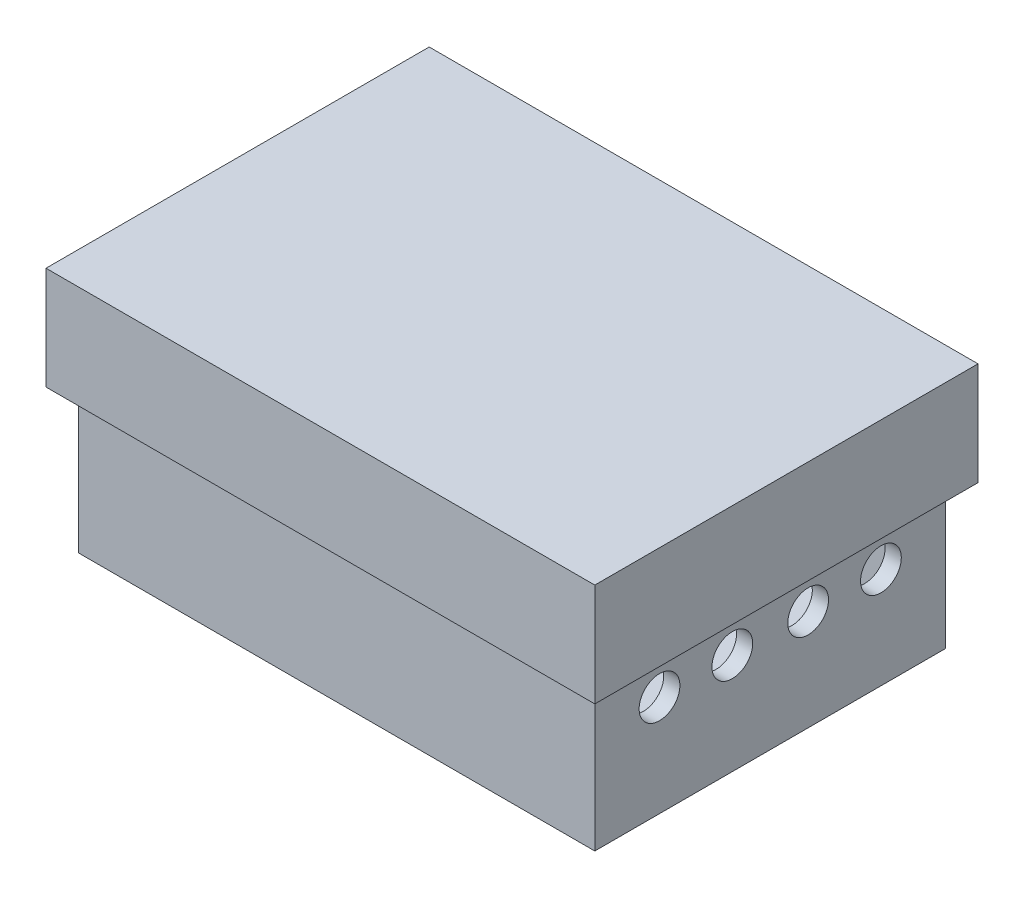
SolidWorks part; units mm, degrees
ref_plane "Front Plane" through (0, 0, 0) normal (0, 0, 1) x (1, 0, 0)
ref_plane "Top Plane" through (0, 0, 0) normal (0, 1, 0) x (1, 0, 0)
ref_plane "Right Plane" through (0, 0, 0) normal (1, 0, 0) x (0, 0, -1)
sketch "Sketch1" plane through (0, 0, 0) normal (0, 1, 0) x (1, 0, 0)
  line L1 (-95, 62.5) -> (95, 62.5)
  line L2 (-95, 62.5) -> (-95, -62.5)
  line L3 (-95, -62.5) -> (95, -62.5)
  line L4 (95, 62.5) -> (95, -62.5)
  line L5 (-95, 62.5) -> (95, -62.5) construction
  line L6 (-95, -62.5) -> (95, 62.5) construction
  line L7 (-101.35, 68.85) -> (101.35, 68.85)
  line L8 (-101.35, 68.85) -> (-101.35, -68.85)
  line L9 (-101.35, -68.85) -> (101.35, -68.85)
  line L10 (101.35, 68.85) -> (101.35, -68.85)
  line L11 (-101.35, 68.85) -> (101.35, -68.85) construction
  line L12 (-101.35, -68.85) -> (101.35, 68.85) construction
  point P0 (0, 0)
  point P6 (0, 0)
  dimension "D1" = 190
  dimension "D2" = 125
  dimension "D3" = 6.35
  dimension "D4" = 6.35
extrude "Boss-Extrude1" add sketch "Sketch1" along normal blind 65
sketch "Sketch2" plane through (0, 0, 0) normal (0, -1, 0) x (1, 0, 0)
  line L0 (-101.35, 68.85) -> (101.35, 68.85) construction
  line L1 (-101.35, 68.85) -> (101.35, 68.85)
  line L2 (101.35, 68.85) -> (101.35, -68.85) construction
  line L3 (101.35, 68.85) -> (101.35, -68.85)
  line L4 (-101.35, -68.85) -> (-101.35, 68.85) construction
  line L5 (-101.35, -68.85) -> (-101.35, 68.85)
  line L6 (101.35, -68.85) -> (-101.35, -68.85) construction
  line L7 (101.35, -68.85) -> (-101.35, -68.85)
extrude "Boss-Extrude2" add sketch "Sketch2" along normal blind 6.35
sketch "Sketch3" plane through (101.35, 0, 0) normal (-1, 0, 0) x (0, 0, 1)
  line L0 (-68.85, 65) -> (68.85, 65) construction
  line L1 (14.875, 33.25) -> (43.45, 33.25) construction
  line L5 (68.85, 65) -> (68.85, -6.35) construction
  circle A0 centre (14.875, 33.25) radius 8
  circle A1 centre (43.45, 33.25) radius 8
  dimension "D1" = 16
  dimension "D3" = 25.4
  dimension "D2" = 28.575
  dimension "D5" = 31.75
extrude "Cut-Extrude1" cut sketch "Sketch3" along normal up to next
mirror "Mirror1" about plane through (0, 0, 0) normal (0, 0, 1) of "Cut-Extrude1"
sketch "Sketch4" plane through (0, 65, 0) normal (0, 1, 0) x (1, 0, 0)
  line L0 (-101.35, 68.85) -> (-101.35, -68.85) construction
  line L1 (107.7, 75.2) -> (-107.7, 75.2)
  line L2 (107.7, 75.2) -> (107.7, -75.2)
  line L3 (107.7, -75.2) -> (-107.7, -75.2)
  line L4 (-107.7, 75.2) -> (-107.7, -75.2)
  line L5 (107.7, 75.2) -> (-107.7, -75.2) construction
  line L6 (107.7, -75.2) -> (-107.7, 75.2) construction
  line L7 (101.35, 68.85) -> (-101.35, 68.85) construction
  line L8 (-101.35, -68.85) -> (101.35, -68.85) construction
  line L9 (101.35, -68.85) -> (101.35, 68.85) construction
  line L10 (-101.35, -68.85) -> (101.35, -68.85)
  line L11 (101.35, -68.85) -> (101.35, 68.85)
  line L12 (101.35, 68.85) -> (-101.35, 68.85)
  line L13 (-101.35, 68.85) -> (-101.35, -68.85)
  point P0 (0, 0)
  dimension "D1" = 6.35
  dimension "D2" = 6.35
extrude "Boss-Extrude3" add sketch "Sketch4" against normal blind 15
sketch "Sketch5" plane through (0, 65, 0) normal (0, 1, 0) x (1, 0, 0)
  line L0 (107.7, 75.2) -> (-107.7, 75.2) construction
  line L1 (107.7, 75.2) -> (-107.7, 75.2)
  line L2 (-107.7, 75.2) -> (-107.7, -75.2) construction
  line L3 (-107.7, 75.2) -> (-107.7, -75.2)
  line L4 (-107.7, -75.2) -> (107.7, -75.2) construction
  line L5 (-107.7, -75.2) -> (107.7, -75.2)
  line L6 (107.7, -75.2) -> (107.7, 75.2) construction
  line L7 (107.7, -75.2) -> (107.7, 75.2)
extrude "Boss-Extrude4" add sketch "Sketch5" along normal blind 25.4
